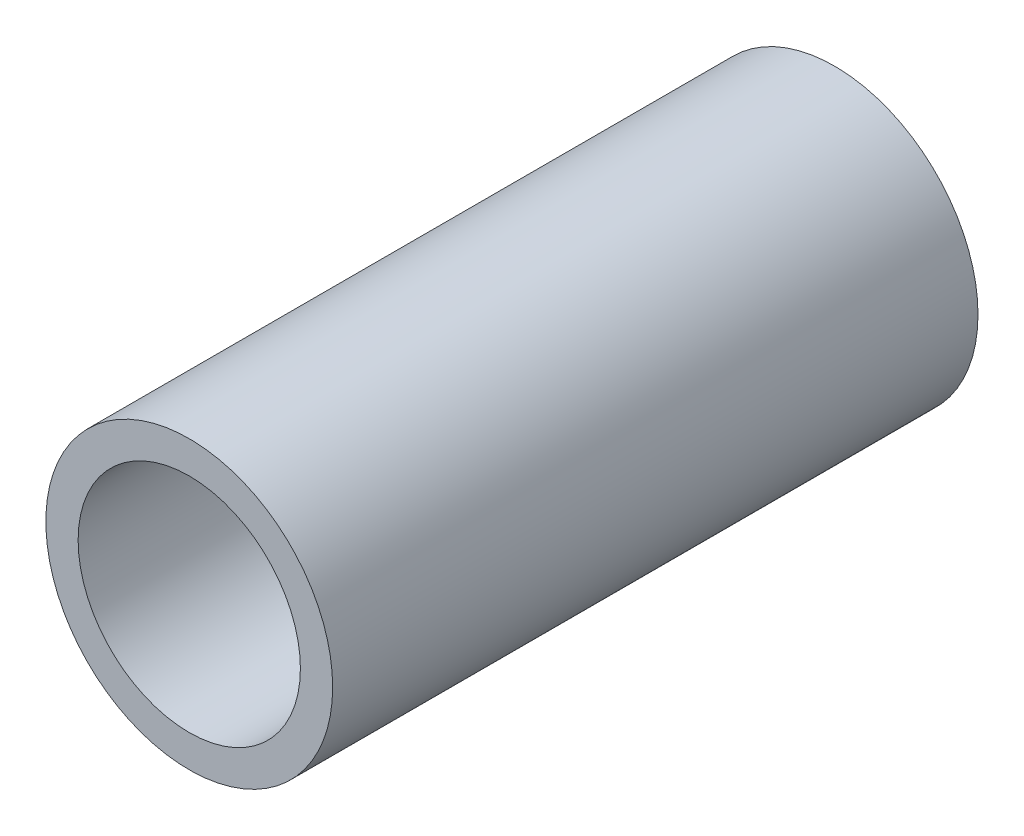
SolidWorks part; units mm, degrees
ref_plane "Спереди" through (0, 0, 0) normal (0, 0, 1) x (1, 0, 0)
ref_plane "Сверху" through (0, 0, 0) normal (0, 1, 0) x (1, 0, 0)
ref_plane "Справа" through (0, 0, 0) normal (1, 0, 0) x (0, 0, -1)
sketch "Эскиз1" plane through (0, 0, 0) normal (0, 0, 1) x (1, 0, 0)
  circle A0 centre (0, 0) radius 1
  circle A1 centre (0, 0) radius 0.775
extrude "Бобышка-Вытянуть1" add sketch "Эскиз1" along normal blind 4.5
